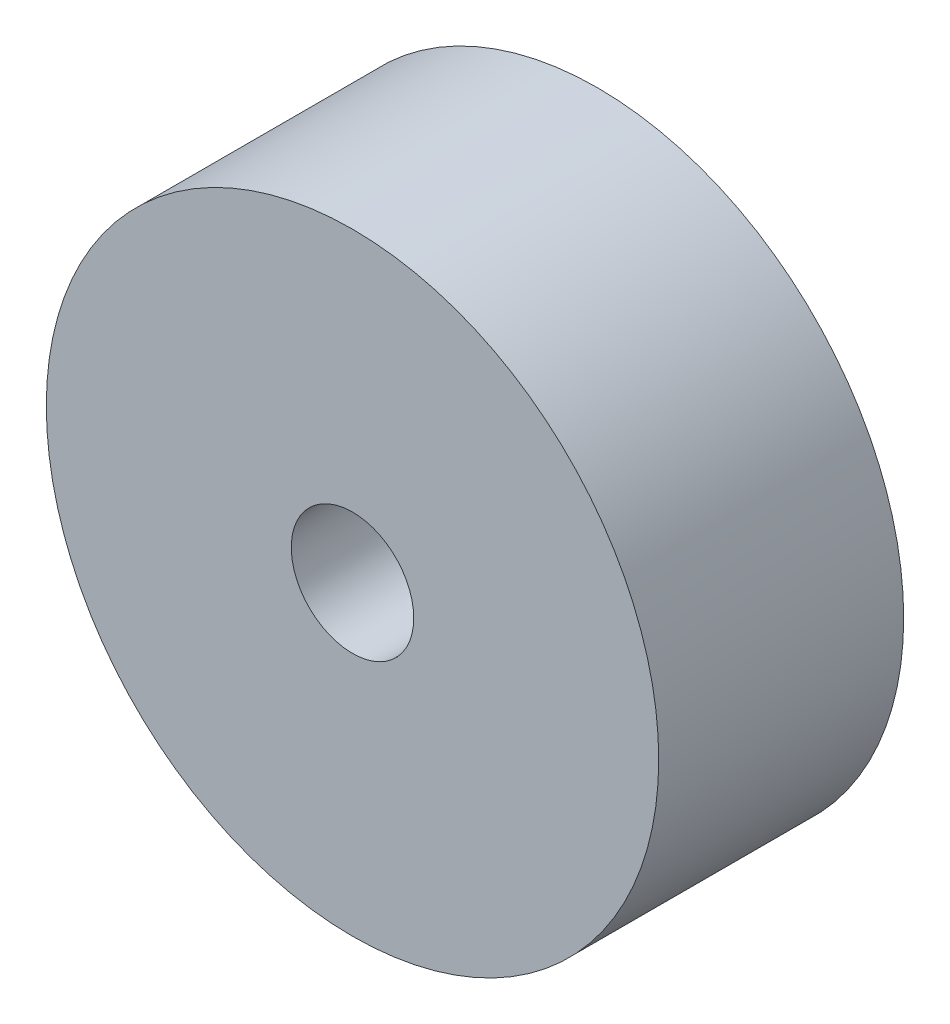
SolidWorks part; units mm, degrees
ref_plane "Front Plane" through (0, 0, 0) normal (0, 0, 1) x (1, 0, 0)
ref_plane "Top Plane" through (0, 0, 0) normal (0, 1, 0) x (1, 0, 0)
ref_plane "Right Plane" through (0, 0, 0) normal (1, 0, 0) x (0, 0, -1)
sketch "Sketch1" plane through (0, 0, 0) normal (0, 0, 1) x (1, 0, 0)
  circle A0 centre (50, 0) radius 15
  dimension "D1" = 30
extrude "Boss-Extrude1" add sketch "Sketch1" along normal blind 12 from offset 4.5 contours A0
sketch "Sketch2" plane through (0, 0, 16.5) normal (0, 0, 1) x (1, 0, 0)
  circle A0 centre (50, 0) radius 3
  dimension "D1" = 6
extrude "Cut-Extrude1" cut sketch "Sketch2" against normal blind 20
